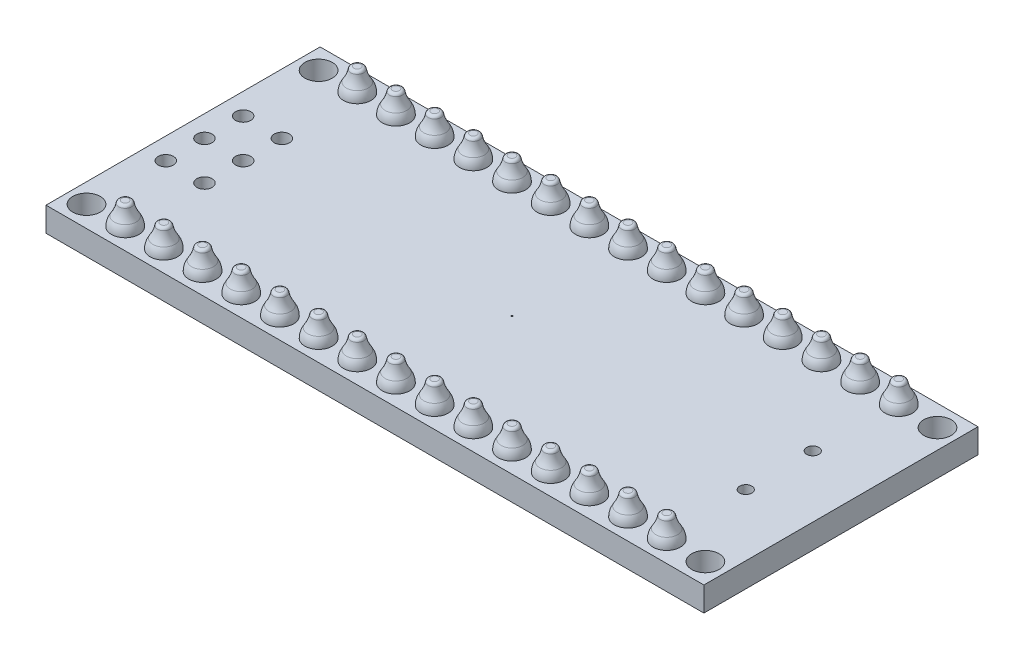
SolidWorks part; units mm, degrees
material "E-Glass Fiber"
ref_plane "Front Plane" through (0, 0, 0) normal (0, 0, 1) x (1, 0, 0)
ref_plane "Top Plane" through (0, 0, 0) normal (0, 1, 0) x (1, 0, 0)
ref_plane "Right Plane" through (0, 0, 0) normal (1, 0, 0) x (0, 0, -1)
sketch "Sketch1" plane through (0, 0, 0) normal (0, 1, 0) x (1, 0, 0)
  line L0 (0, 7.62) -> (-3.82, 7.62) construction
  line L1 (-3.82, 16.62) -> (39.38, 16.62)
  line L2 (-3.82, 16.62) -> (-3.82, -1.38)
  line L3 (-3.82, -1.38) -> (39.38, -1.38)
  line L4 (39.38, 16.62) -> (39.38, -1.38)
  line L5 (0, 0) -> (35.56, 0) construction
  line L6 (0, 0) -> (0, 15.24) construction
  line L7 (0, 15.24) -> (35.56, 15.24) construction
  line L8 (35.56, 0) -> (35.56, 15.24) construction
  line L10 (35.56, 7.62) -> (39.38, 7.62) construction
  circle A0 centre (17.78, 7.62) radius 0.05
  point P12 (17.78, 7.62)
  dimension "D5" = 0.1
  dimension "D1" = 43.2
  dimension "D2" = 18
  dimension "D3" = 15.24
  dimension "D4" = 35.56
extrude "Boss-Extrude2" add sketch "Sketch1" along normal blind 1.6
sketch "Sketch2" plane through (0, 0, 0) normal (0, 1, 0) x (1, 0, 0)
  line L0 (0, -0.88) -> (0, 0.88) construction
  line L2 (-0.88, 0) -> (0.88, 0) construction
  circle A0 centre (0, 0) radius 0.45
  circle A1 centre (0, 15.24) radius 0.45
  dimension "D1" = 0.9
  dimension "D2" = 15.24
extrude "Cut-Extrude2" cut sketch "Sketch2" along normal blind 1.6
pattern_linear "LPattern1" count 15 spacing 2.54 along (1, 0, 0) of "Cut-Extrude2"
sketch "Sketch3" plane through (0, 0, 0) normal (0, 1, 0) x (1, 0, 0)
  line L1 (-0.88, 0) -> (0.88, 0) construction
  line L2 (0, -0.88) -> (0, 0.88) construction
  circle A0 centre (0.127, 10.16) radius 0.5
  circle A1 centre (-2.413, 10.16) radius 0.5
  circle A2 centre (-2.413, 7.62) radius 0.5
  circle A3 centre (-2.413, 5.08) radius 0.5
  circle A4 centre (0.127, 5.08) radius 0.5
  circle A5 centre (0.127, 7.62) radius 0.5
  dimension "D1" = 1
  dimension "D5" = 7.62
  dimension "D2" = 2.54
  dimension "D3" = 2.54
  dimension "D4" = 2.54
  dimension "D6" = 2.54
  dimension "D7" = 0.127
extrude "Cut-Extrude4" cut sketch "Sketch3" along normal blind 1.6
sketch "Sketch4" plane through (0, 0, 0) normal (0, 1, 0) x (1, 0, 0)
  line L0 (-0.88, 0) -> (0.88, 0) construction
  line L1 (0, -0.88) -> (0, 0.88) construction
  circle A0 centre (38.1, 15.24) radius 0.9
  circle A1 centre (38.1, 0) radius 0.9
  circle A2 centre (-2.54, 0) radius 0.9
  circle A3 centre (-2.54, 15.24) radius 0.9
  dimension "D3" = 1.8
  dimension "D1" = 40.64
  dimension "D2" = 2.54
  dimension "D4" = 15.24
  dimension "D5" = 15.24
extrude "Cut-Extrude5" cut sketch "Sketch4" along normal blind 1.6
sketch "Sketch5" plane through (0, 1.6, 0) normal (0, 1, 0) x (1, 0, 0)
  circle A0 centre (38.1, 15.24) radius 0.9
  circle A1 centre (38.1, 15.24) radius 1.275
  circle A2 centre (38.1, 15.24) radius 0.9 construction
  circle A3 centre (38.1, 0) radius 0.9
  circle A4 centre (38.1, 0) radius 0.9 construction
  circle A5 centre (38.1, 0) radius 1.275
  circle A6 centre (-2.54, 15.24) radius 0.9
  circle A7 centre (-2.54, 15.24) radius 1.275
  circle A8 centre (-2.54, 0) radius 0.9
  circle A9 centre (-2.54, 0) radius 1.275
  circle A10 centre (-2.54, 15.24) radius 0.9 construction
  circle A11 centre (-2.54, 0) radius 0.9 construction
  dimension "D1" = 2.55
extrude "Boss-Extrude3" [suppressed] add sketch "Sketch5" along normal blind 0.1
sketch "Sketch6" plane through (0, 0, 0) normal (1, 0, 0) x (0, 0, -1)
  line L0 (0, 1.6) -> (0.9, 1.6)
  line L1 (-1.38, 1.6) -> (16.62, 1.6) construction
  line L2 (0.2252, 3.1) -> (0, 3.1)
  line L3 (0, 55) -> (0, -55) construction
  line L4 (0, 3.1) -> (0, 1.6)
  line L5 (0, 1.3722) -> (0, 3.4408) construction
  arc A0 (0.9, 1.6) -> (0.7139, 2.2122) centre (-0.2, 1.6) ccw
  arc A1 (0.7139, 2.2122) -> (0.4221, 2.9352) centre (2.2924, 3.2697) cw
  arc A2 (0.4221, 2.9352) -> (0.2252, 3.1) centre (0.2252, 2.9) ccw
  point P16 (0.4, 3.1)
  dimension "D4" = 1.1
  dimension "D5" = 1.9
  dimension "D6" = 0.2
  dimension "D1" = 1.5
  dimension "D2" = 0.8
  dimension "D3" = 1.8
revolve "Revolve1" add sketch "Sketch6" angle 360 about L5
pattern_linear "LPattern2" count 2 spacing 15.24 along (0, 0, -1) count 15 spacing 2.54 along (1, 0, 0) of "Revolve1"
ref_plane "Plane3" through (0, 0, -5.08) normal (0, 0, 1) x (1, 0, 0)
sketch "Sketch7" plane through (0, 0, -5.08) normal (0, 0, 1) x (1, 0, 0)
  line L0 (0.127, 3.889) -> (0.127, -2.5597) construction
  line L2 (0, -1.705) -> (0, 1.705) construction
  line L3 (0.127, 0) -> (1.027, 0)
  line L4 (9.9, 0) -> (-9.9, 0) construction
  line L5 (0.127, 0) -> (0.127, -1.5)
  line L6 (0.127, -1.5) -> (0.3395, -1.5)
  arc A0 (0.538, -1.325) -> (0.807, -0.66) centre (1.927, -1.5) cw
  arc A1 (0.807, -0.66) -> (1.027, 0) centre (-0.073, 0) ccw
  arc A2 (0.3395, -1.5) -> (0.538, -1.325) centre (0.3395, -1.3) ccw
  point P16 (0.527, -1.5)
  dimension "D5" = 1.1
  dimension "D6" = 0.2
  dimension "D1" = 0.127
  dimension "D2" = 1.5
  dimension "D3" = 0.8
  dimension "D4" = 1.8
revolve "Revolve2" add sketch "Sketch7" angle 360 about L0
pattern_linear "LPattern3" count 2 spacing 2.54 along (-1, 0, 0) count 3 spacing 2.54 along (0, 0, -1) of "Revolve2"
sketch "Sketch8" plane through (0, 0, 0) normal (0, -1, 0) x (1, 0, 0)
  circle A0 centre (38.1, 0) radius 0.9
  circle A1 centre (38.1, 0) radius 1.275
  circle A2 centre (38.1, -15.24) radius 1.275
  circle A3 centre (38.1, -15.24) radius 0.9
  circle A4 centre (38.1, -15.24) radius 0.9 construction
  circle A5 centre (38.1, 0) radius 0.9 construction
  circle A6 centre (-2.54, 0) radius 0.9
  circle A7 centre (-2.54, 0) radius 1.275
  circle A8 centre (-2.54, -15.24) radius 0.9
  circle A9 centre (-2.54, -15.24) radius 1.275
  circle A10 centre (-2.54, 0) radius 0.9 construction
  circle A11 centre (-2.54, -15.24) radius 0.9 construction
  dimension "D1" = 2.55
extrude "Boss-Extrude4" [suppressed] add sketch "Sketch8" along normal blind 0.1
sketch "Sketch9" plane through (0, 0, 0) normal (0, 1, 0) x (1, 0, 0)
  line L0 (-55, 0) -> (55, 0) construction
  line L1 (39.38, -1.38) -> (39.38, 16.62) construction
  circle A0 centre (35.33, 5.42) radius 0.4
  circle A1 centre (35.33, 9.82) radius 0.4
  dimension "D1" = 0.8
  dimension "D2" = 4.4
  dimension "D3" = 5.42
  dimension "D4" = 4.05
extrude "Cut-Extrude6" cut sketch "Sketch9" along normal blind 10
